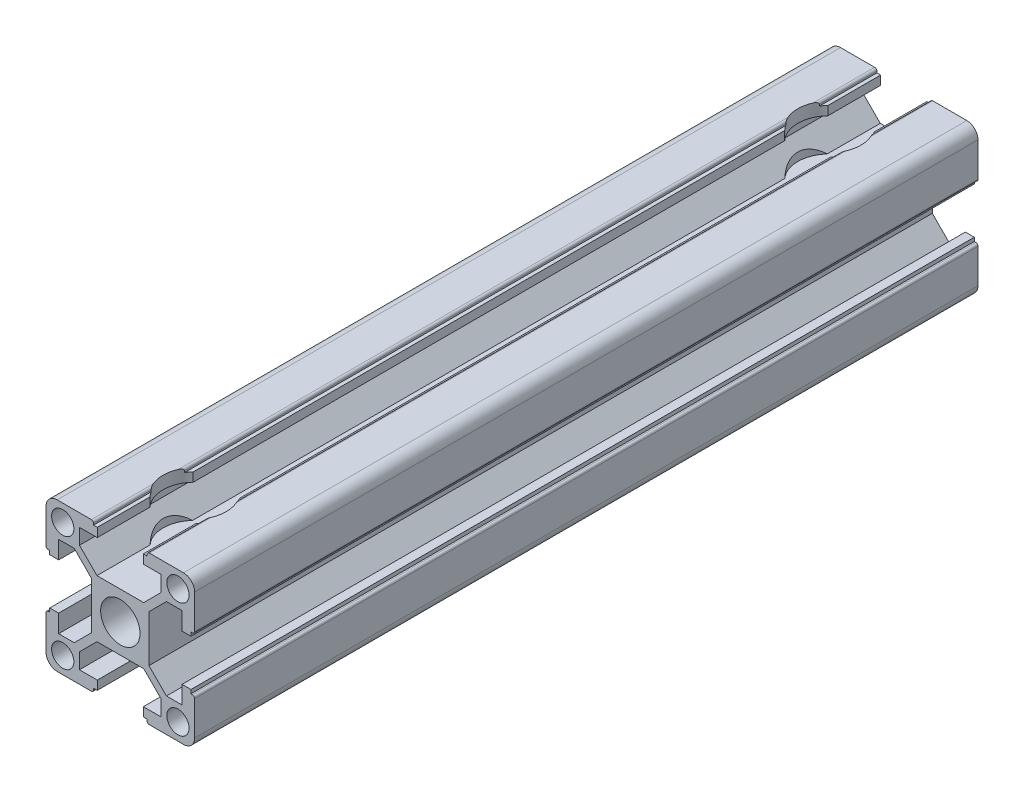
SolidWorks part; units mm, degrees
ref_plane "前视基准面" through (0, 0, 0) normal (0, 0, 1) x (1, 0, 0)
ref_plane "上视基准面" through (0, 0, 0) normal (0, 1, 0) x (1, 0, 0)
ref_plane "右视基准面" through (0, 0, 0) normal (1, 0, 0) x (0, 0, -1)
sketch "草图1" plane through (0, 0, 0) normal (0, 0, 1) x (1, 0, 0)
  line L0 (-7.75, 0) -> (0, 0) construction
  line L1 (7.75, -7.75) -> (-7.75, -7.75) construction
  line L2 (7.75, -7.75) -> (7.75, 7.75) construction
  line L3 (7.75, 7.75) -> (-7.75, 7.75) construction
  line L4 (-7.75, -7.75) -> (-7.75, 7.75) construction
  line L5 (7.75, -7.75) -> (-7.75, 7.75) construction
  line L6 (7.75, 7.75) -> (-7.75, -7.75) construction
  line L7 (0, 0) -> (0, 7.75) construction
  line L8 (3.1429, 3.85) -> (-3.1429, 3.85)
  line L9 (-3.1429, 3.85) -> (-5.5, 6.2071)
  line L10 (-5.5, 6.2071) -> (-5.5, 8.3)
  line L11 (-5.5, 8.3) -> (-3.1, 8.3)
  line L12 (-3.1, 8.3) -> (-3.1, 9.5)
  line L13 (-3.1, 9.5) -> (-3.6, 9.5)
  line L14 (-3.6, 9.5) -> (-3.6, 9.7)
  line L15 (-3.9, 10) -> (-8.5, 10)
  line L16 (-3.85, -3.1429) -> (-3.85, 3.1429)
  line L17 (-3.85, 3.1429) -> (-6.2071, 5.5)
  line L18 (-6.2071, 5.5) -> (-8.3, 5.5)
  line L19 (-8.3, 5.5) -> (-8.3, 3.1)
  line L20 (-9.5, 3.1) -> (-9.5, 3.6)
  line L21 (-8.3, 3.1) -> (-9.5, 3.1)
  line L22 (-9.5, 3.6) -> (-9.7, 3.6)
  line L23 (-10, 3.9) -> (-10, 8.5)
  line L24 (5.5, 8.3) -> (3.1, 8.3)
  line L25 (3.6, 9.5) -> (3.6, 9.7)
  line L26 (3.1, 9.5) -> (3.6, 9.5)
  line L27 (3.1, 8.3) -> (3.1, 9.5)
  line L28 (5.5, 6.2071) -> (5.5, 8.3)
  line L29 (3.1429, 3.85) -> (5.5, 6.2071)
  line L30 (3.85, -3.1429) -> (3.85, 3.1429)
  line L31 (3.85, 3.1429) -> (6.2071, 5.5)
  line L32 (9.5, 3.6) -> (9.7, 3.6)
  line L33 (8.3, 3.1) -> (9.5, 3.1)
  line L34 (9.5, 3.1) -> (9.5, 3.6)
  line L35 (8.3, 5.5) -> (8.3, 3.1)
  line L36 (6.2071, 5.5) -> (8.3, 5.5)
  line L37 (10, 3.9) -> (10, 8.5)
  line L38 (3.9, 10) -> (8.5, 10)
  line L39 (-9.5, -3.6) -> (-9.7, -3.6)
  line L40 (-8.3, -3.1) -> (-9.5, -3.1)
  line L41 (-9.5, -3.1) -> (-9.5, -3.6)
  line L42 (-8.3, -5.5) -> (-8.3, -3.1)
  line L43 (-6.2071, -5.5) -> (-8.3, -5.5)
  line L44 (-3.85, -3.1429) -> (-6.2071, -5.5)
  line L45 (-3.1429, -3.85) -> (-5.5, -6.2071)
  line L46 (-5.5, -6.2071) -> (-5.5, -8.3)
  line L47 (-3.6, -9.5) -> (-3.6, -9.7)
  line L48 (-3.1, -9.5) -> (-3.6, -9.5)
  line L49 (-3.1, -8.3) -> (-3.1, -9.5)
  line L50 (-5.5, -8.3) -> (-3.1, -8.3)
  line L51 (5.5, -6.2071) -> (5.5, -8.3)
  line L52 (3.1, -8.3) -> (3.1, -9.5)
  line L53 (3.1, -9.5) -> (3.6, -9.5)
  line L54 (3.6, -9.5) -> (3.6, -9.7)
  line L55 (5.5, -8.3) -> (3.1, -8.3)
  line L56 (3.1429, -3.85) -> (5.5, -6.2071)
  line L57 (3.1429, -3.85) -> (-3.1429, -3.85)
  line L58 (3.85, -3.1429) -> (6.2071, -5.5)
  line L59 (6.2071, -5.5) -> (8.3, -5.5)
  line L60 (8.3, -5.5) -> (8.3, -3.1)
  line L61 (9.5, -3.1) -> (9.5, -3.6)
  line L62 (8.3, -3.1) -> (9.5, -3.1)
  line L63 (9.5, -3.6) -> (9.7, -3.6)
  line L64 (3.9, -10) -> (8.5, -10)
  line L65 (10, -3.9) -> (10, -8.5)
  line L66 (-10, -3.9) -> (-10, -8.5)
  line L67 (-3.9, -10) -> (-8.5, -10)
  circle A0 centre (0, 0) radius 2.65
  circle A1 centre (-7.75, 7.75) radius 1.5
  circle A2 centre (7.75, 7.75) radius 1.5
  circle A3 centre (7.75, -7.75) radius 1.5
  circle A4 centre (-7.75, -7.75) radius 1.5
  arc A5 (-10, -8.5) -> (-8.5, -10) centre (-8.5, -8.5) ccw
  arc A6 (8.5, -10) -> (10, -8.5) centre (8.5, -8.5) ccw
  arc A7 (10, 8.5) -> (8.5, 10) centre (8.5, 8.5) ccw
  arc A8 (-8.5, 10) -> (-10, 8.5) centre (-8.5, 8.5) ccw
  arc A9 (3.6, -9.7) -> (3.9, -10) centre (3.9, -9.7) ccw
  arc A10 (-3.6, -9.7) -> (-3.9, -10) centre (-3.9, -9.7) cw
  arc A11 (-9.7, -3.6) -> (-10, -3.9) centre (-9.7, -3.9) ccw
  arc A12 (9.7, -3.6) -> (10, -3.9) centre (9.7, -3.9) cw
  arc A13 (9.7, 3.6) -> (10, 3.9) centre (9.7, 3.9) ccw
  arc A14 (-9.7, 3.6) -> (-10, 3.9) centre (-9.7, 3.9) cw
  arc A15 (3.6, 9.7) -> (3.9, 10) centre (3.9, 9.7) cw
  arc A16 (-3.6, 9.7) -> (-3.9, 10) centre (-3.9, 9.7) ccw
  point P46 (0, 3.85)
  point P56 (-3.85, 0)
  point P78 (3.85, 0)
  point P87 (-10, -10)
  point P90 (10, -10)
  point P93 (10, 10)
  point P96 (-10, 10)
  point P99 (3.6, -10)
  point P102 (-3.6, -10)
  point P105 (-10, -3.6)
  point P108 (10, -3.6)
  point P111 (10, 3.6)
  point P114 (-10, 3.6)
  point P117 (3.6, 10)
  point P120 (-3.6, 10)
  dimension "D1" = 5.3
  dimension "D2" = 3
  dimension "D11" = 1.5
  dimension "D12" = 2.25
  dimension "D13" = 0.3
  dimension "D3" = 7.7
  dimension "D4" = 6.2
  dimension "D5" = 1.7
  dimension "D6" = 1.2
  dimension "D7" = 20
  dimension "D8" = 7.2
  dimension "D9" = 11
  dimension "D10" = 1
extrude "凸台-拉伸1" add sketch "草图1" along normal mid plane 105.4
sketch "草图2" plane through (0, -3.85, 0) normal (0, -1, 0) x (1, 0, 0)
  line L0 (0, -42.7) -> (0, 42.7) construction
  circle A0 centre (0, 42.7) radius 2.1
  circle A1 centre (0, -42.7) radius 2.1
  point P5 (0, 0)
  dimension "D1" = 85.4
  dimension "D2" = 4.2
extrude "切除-拉伸1" cut sketch "草图2" against normal through all
sketch "草图3" plane through (0, 3.85, 0) normal (0, 1, 0) x (1, 0, 0)
  circle A0 centre (0, 42.7) radius 4.25
  circle A1 centre (0, -42.7) radius 4.25
  dimension "D1" = 8.5
extrude "切除-拉伸2" cut sketch "草图3" along normal up to surface (6.15 mm away) up to face at (6.2, 10, 0)
sketch "草图4" plane through (3.85, 0, 0) normal (1, 0, 0) x (0, 0, -1)
  line L0 (38.1, 0) -> (-38.1, 0) construction
  line L1 (-52.7, -3.1429) -> (-52.7, 3.1429) construction
  circle A0 centre (-38.1, 0) radius 2
  circle A1 centre (38.1, 0) radius 2
  point P4 (0, 0)
  dimension "D1" = 4
  dimension "D2" = 14.6
extrude "切除-拉伸3" cut sketch "草图4" against normal through all
